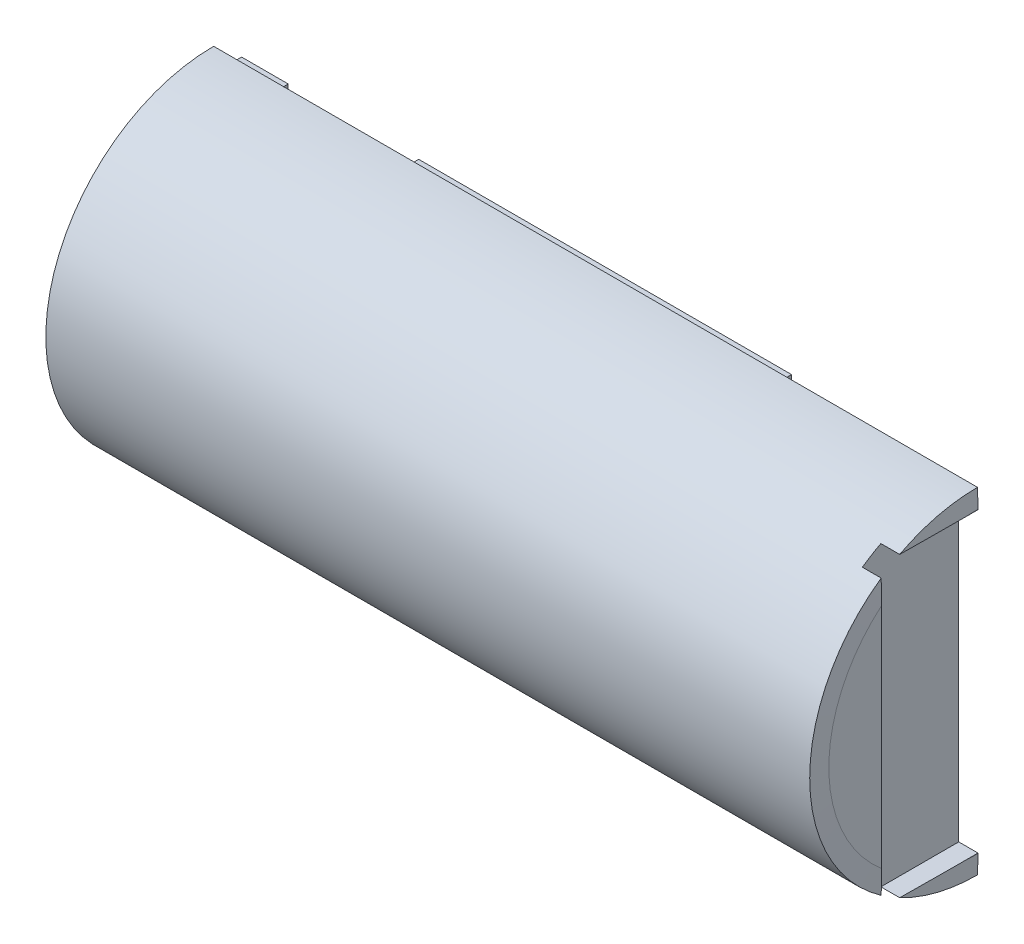
SolidWorks part; units mm, degrees
ref_plane "Front Plane" through (0, 0, 0) normal (0, 0, 1) x (1, 0, 0)
ref_plane "Top Plane" through (0, 0, 0) normal (0, 1, 0) x (1, 0, 0)
ref_plane "Right Plane" through (0, 0, 0) normal (1, 0, 0) x (0, 0, -1)
sketch "Sketch2" plane through (0, 0, 0) normal (0, 0, 1) x (1, 0, 0)
  line L0 (0, 0) -> (0, 40.64)
  line L1 (0, 0) -> (5.08, 0)
  line L2 (5.08, 0) -> (5.08, 40.64)
  line L3 (0, 40.64) -> (0, 45.72)
  line L4 (0, 45.72) -> (25.4, 45.72)
  line L6 (5.08, 40.64) -> (25.4, 40.64)
  line L8 (208.1, 45.72) -> (195.4, 45.72)
  line L9 (195.4, 45.72) -> (25.4, 45.72)
  line L10 (208.2277, 40.64) -> (195.5277, 40.64)
  line L11 (195.5277, 40.64) -> (25.4, 40.64)
  line L12 (208.1, 45.72) -> (208.2277, 40.64)
  dimension "D8" = 5.08
  dimension "D1" = 40.64
  dimension "D2" = 5.08
  dimension "D3" = 40.64
  dimension "D4" = 5.08
  dimension "D5" = 25.4
  dimension "D6" = 170
  dimension "D7" = 12.7
  dimension "D9" = 180
  dimension "D10" = 12.7
revolve "Revolve2" add sketch "Sketch2" angle 180 about L1
sketch "Sketch5" plane through (0, 0, 0) normal (0, 0, -1) x (-1, 0, 0)
  line L0 (-5.08, 40.64) -> (0, 40.64) construction
  line L1 (-3.81, 40.64) -> (-1.27, 40.64)
  line L2 (-3.81, 40.64) -> (-3.81, 27.94)
  line L3 (-3.81, 27.94) -> (-1.27, 27.94)
  line L4 (-1.27, 40.64) -> (-1.27, 27.94)
  line L5 (0, -45.72) -> (0, 45.72) construction
  line L6 (-5.08, 40.64) -> (-5.08, 45.72) construction
  line L7 (-208.1, 45.72) -> (0, 45.72) construction
  line L8 (-154.9139, -41.91) -> (-154.9139, -44.45)
  line L9 (-5.08, 44.45) -> (-17.78, 44.45)
  line L10 (-5.08, 44.45) -> (-5.08, 41.91)
  line L11 (-5.08, 41.91) -> (-17.78, 41.91)
  line L12 (-17.78, 44.45) -> (-17.78, 41.91)
  line L13 (-154.9139, -44.45) -> (-53.3139, -44.45)
  line L14 (-53.3139, -44.45) -> (-53.3139, -41.91)
  line L15 (-53.3139, -41.91) -> (-154.9139, -41.91)
  line L16 (-312.3416, -45.72) -> (104.1139, -45.72) construction
  line L17 (-53.3139, -41.91) -> (-53.3139, -45.72) construction
  line L18 (-53.3139, -44.45) -> (-53.3139, -40.64) construction
  line L19 (104.1139, -40.64) -> (-312.3416, -40.64) construction
  line L20 (-154.9139, -40.64) -> (-154.9139, -44.45) construction
  line L21 (-154.9139, -41.91) -> (-154.9139, -45.72) construction
  line L22 (0, 0) -> (-208.2277, 0) construction
  line L23 (-208.2277, -40.64) -> (-208.2277, 40.64) construction
  line L24 (-53.3139, 44.45) -> (-53.3139, 41.91)
  line L25 (-154.9139, 44.45) -> (-53.3139, 44.45)
  line L26 (-154.9139, 41.91) -> (-154.9139, 44.45)
  line L27 (-53.3139, 41.91) -> (-154.9139, 41.91)
  line L28 (-5.08, -41.91) -> (-17.78, -41.91)
  line L29 (-17.78, -44.45) -> (-17.78, -41.91)
  line L30 (-5.08, -44.45) -> (-17.78, -44.45)
  line L31 (-5.08, -44.45) -> (-5.08, -41.91)
  line L32 (-3.81, -27.94) -> (-1.27, -27.94)
  line L33 (-1.27, -40.64) -> (-1.27, -27.94)
  line L34 (-3.81, -40.64) -> (-1.27, -40.64)
  line L35 (-3.81, -40.64) -> (-3.81, -27.94)
  point P9 (-2.54, 40.64)
  point P10 (-2.54, 40.64)
  point P18 (-5.08, 43.18)
  point P19 (-5.08, 43.18)
  point P26 (-104.1139, -45.72)
  point P27 (-104.1139, -41.91)
  dimension "D1" = 12.7
  dimension "D2" = 2.54
  dimension "D3" = 12.7
  dimension "D4" = 2.54
  dimension "D5" = 2.54
  dimension "D6" = 2.54
  dimension "D7" = 101.6
extrude "Boss-Extrude1" add sketch "Sketch5" along normal blind 2.54 contours L15 L8 L13 L14 | L10 L9 L12 L11 | L2 L1 L4 L3 | L32 L33 L34 L35 | L28 L29 L30 L31 | L24 L27 L26 L25
sketch "Sketch7" plane through (0, 0, 0) normal (-1, 0, 0) x (0, 0, 1)
  line L0 (0, 25) -> (0, -25)
  line L1 (0, 25) -> (20, 25)
  line L2 (0, -25) -> (20, -25)
  line L3 (20, 25) -> (20, -25)
  line L4 (0, -45.72) -> (0, 45.72) construction
  point P6 (0, 0)
  dimension "D1" = 50
  dimension "D2" = 20
extrude "Cut-Extrude1" cut sketch "Sketch7" against normal blind 7
sketch "Sketch8" plane through (0, 0, 0) normal (0, 0, -1) x (-1, 0, 0)
  line L0 (-208.1, 45.72) -> (0, 45.72) construction
  line L1 (-13.08, 45.72) -> (-18.08, 45.72)
  line L2 (-13.08, 45.72) -> (-13.08, -45.72)
  line L3 (-13.08, -45.72) -> (-18.08, -45.72)
  line L4 (-18.08, 45.72) -> (-18.08, -45.72)
  line L5 (-5.08, 40.64) -> (-5.08, 25) construction
  line L8 (-208.1, -45.72) -> (0, -45.72) construction
  dimension "D1" = 5
  dimension "D3" = 8
extrude "Boss-Extrude3" add sketch "Sketch8" against normal up to next
sketch "Sketch9" plane through (5.08, 0, 0) normal (1, 0, 0) x (0, 0, -1)
  line L1 (-0.8418, 37.9918) -> (-6.9711, 37.9918)
  line L2 (-0.8418, 37.9918) -> (-0.8418, 29.9132)
  line L3 (-0.8418, 29.9132) -> (-6.9711, 29.9132)
  line L4 (-6.9711, 37.9918) -> (-6.9711, 29.9132)
extrude "Boss-Extrude4" add sketch "Sketch9" along normal blind 2
sketch "Sketch12" plane through (13.08, 0, 0) normal (-1, 0, 0) x (0, 0, 1)
  line L0 (23.64, 33.0569) -> (23.64, -33.0569)
  line L1 (20, -25) -> (20, 25) construction
  arc A0 (23.64, 33.0569) -> (23.64, -33.0569) centre (0, 0) cw
  arc A2 (0, -40.64) -> (0, 40.64) centre (0, 0) ccw construction
  point P3 (23.64, 0)
  point P5 (40.64, 0)
  dimension "D1" = 17
extrude "Boss-Extrude7" add sketch "Sketch12" along normal up to surface (8 mm away) up to face at (5.08, 0, 13.44)
sketch "Sketch13" plane through (0, 0, 0) normal (0, 0, -1) x (-1, 0, 0)
  line L0 (-18.08, -40.64) -> (-208.2277, -40.64) construction
  line L1 (-113.1539, 27.5) -> (-183.1539, 27.5)
  line L2 (-113.1539, 27.5) -> (-113.1539, -27.5)
  line L3 (-113.1539, -27.5) -> (-183.1539, -27.5)
  line L4 (-183.1539, 27.5) -> (-183.1539, -27.5)
  line L5 (-110.6139, 30.04) -> (-185.6939, 30.04)
  line L6 (-110.6139, 30.04) -> (-110.6139, -30.04)
  line L7 (-110.6139, -30.04) -> (-185.6939, -30.04)
  line L8 (-185.6939, 30.04) -> (-185.6939, -30.04)
  line L9 (-113.1539, 40.64) -> (-113.1539, -40.64) construction
  line L10 (-18.08, 40.64) -> (-208.2277, 40.64) construction
  point P14 (-113.1539, 0)
  point P15 (-113.1539, 0)
  dimension "D1" = 55
  dimension "D2" = 70
  dimension "D3" = 2.54
  dimension "D4" = 2.54
  dimension "D5" = 2.54
  dimension "D6" = 2.54
extrude "Boss-Extrude8" add sketch "Sketch13" against normal up to surface (29.9226 mm away)
sketch "Sketch14" plane through (0, 0, 0) normal (0, 0, -1) x (-1, 0, 0)
  line L1 (-110.6139, 30.04) -> (-185.6939, 30.04)
  line L2 (-110.6139, 30.04) -> (-110.6139, -30.04)
  line L3 (-110.6139, -30.04) -> (-185.6939, -30.04)
  line L4 (-185.6939, 30.04) -> (-185.6939, -30.04)
extrude "Cut-Extrude3" cut sketch "Sketch14" against normal blind 11
sketch "Sketch15" plane through (0, 0, 11) normal (0, 0, -1) x (-1, 0, 0)
  line L1 (-113.1539, 27.5) -> (-183.1539, 27.5)
  line L2 (-113.1539, 27.5) -> (-113.1539, -27.5)
  line L3 (-113.1539, -27.5) -> (-183.1539, -27.5)
  line L4 (-183.1539, 27.5) -> (-183.1539, -27.5)
extrude "Boss-Extrude9" add sketch "Sketch15" against normal up to next
sketch "Sketch17" plane through (0, 0, 11) normal (0, 0, -1) x (-1, 0, 0)
  line L0 (-110.6139, 30.04) -> (-185.6939, 30.04) construction
  line L1 (-113.1539, 27.5) -> (-183.1539, 27.5)
  line L2 (-113.1539, 27.5) -> (-113.1539, -27.5)
  line L3 (-113.1539, -27.5) -> (-183.1539, -27.5)
  line L4 (-183.1539, 27.5) -> (-183.1539, 19.5)
  line L5 (-185.6939, 30.04) -> (-185.6939, -30.04) construction
  line L6 (-185.6939, -30.04) -> (-110.6139, -30.04) construction
  line L7 (-110.6139, -30.04) -> (-110.6139, 30.04) construction
  line L8 (-183.1539, 5.5) -> (-183.1539, -13.5)
  line L9 (-183.1539, 19.5) -> (-185.6939, 19.5)
  line L11 (-183.1539, 5.5) -> (-185.6939, 5.5)
  line L12 (-185.6939, 19.5) -> (-185.6939, 5.5)
  line L13 (-183.1539, -24.5) -> (-185.6939, -24.5)
  line L15 (-183.1539, -13.5) -> (-185.6939, -13.5)
  line L16 (-185.6939, -24.5) -> (-185.6939, -13.5)
  line L17 (-183.1539, -24.5) -> (-183.1539, -27.5)
  dimension "D1" = 2.54
  dimension "D2" = 2.54
  dimension "D3" = 2.54
  dimension "D4" = 2.54
  dimension "D5" = 8
  dimension "D6" = 22
  dimension "D7" = 14
  dimension "D8" = 3
extrude "Cut-Extrude5" cut sketch "Sketch17" against normal blind 15
sketch "Sketch18" plane through (18.08, 0, 0) normal (1, 0, 0) x (0, 0, -1)
  line L0 (0, 40.64) -> (0, -40.64) construction
  line L1 (0, 17.9952) -> (-12, 17.9952)
  line L2 (0, 17.9952) -> (0, -38.0048)
  line L3 (0, -38.0048) -> (-12, -38.0048)
  line L4 (-12, 17.9952) -> (-12, -38.0048)
  dimension "D1" = 12
  dimension "D2" = 56
  dimension "D3" = 2.6352
extrude "Cut-Extrude6" cut sketch "Sketch18" against normal up to next
sketch "Sketch23" plane through (0, 0, 0) normal (0, 0, -1) x (-1, 0, 0)
  line L0 (-18.08, -40.64) -> (-208.2277, -40.64) construction
  line L1 (-208.2277, 40.64) -> (-198.2277, 40.64)
  line L2 (-208.2277, 40.64) -> (-208.2277, -40.64)
  line L3 (-208.2277, -40.64) -> (-198.2277, -40.64)
  line L4 (-198.2277, 40.64) -> (-198.2277, -40.64)
  dimension "D1" = 10
extrude "Boss-Extrude10" add sketch "Sketch23" against normal up to surface up to face at (9.08, -37.7731, 12.1166)
sketch "Sketch24" plane through (208.2277, 0, 0) normal (1, 0, 0) x (0, 0, -1)
  line L0 (0, 40.64) -> (0, -40.64) construction
  line L1 (-26.25, -40.5) -> (0, -40.5)
  line L2 (-26.25, -40.5) -> (-26.25, 40.5)
  line L3 (-26.25, 40.5) -> (0, 40.5)
  line L4 (0, -40.5) -> (0, 40.5)
  point P4 (0, 0)
  point P7 (0, 0)
  dimension "D1" = 81
  dimension "D2" = 26.25
extrude "Cut-Extrude7" cut sketch "Sketch24" against normal blind 5.25
